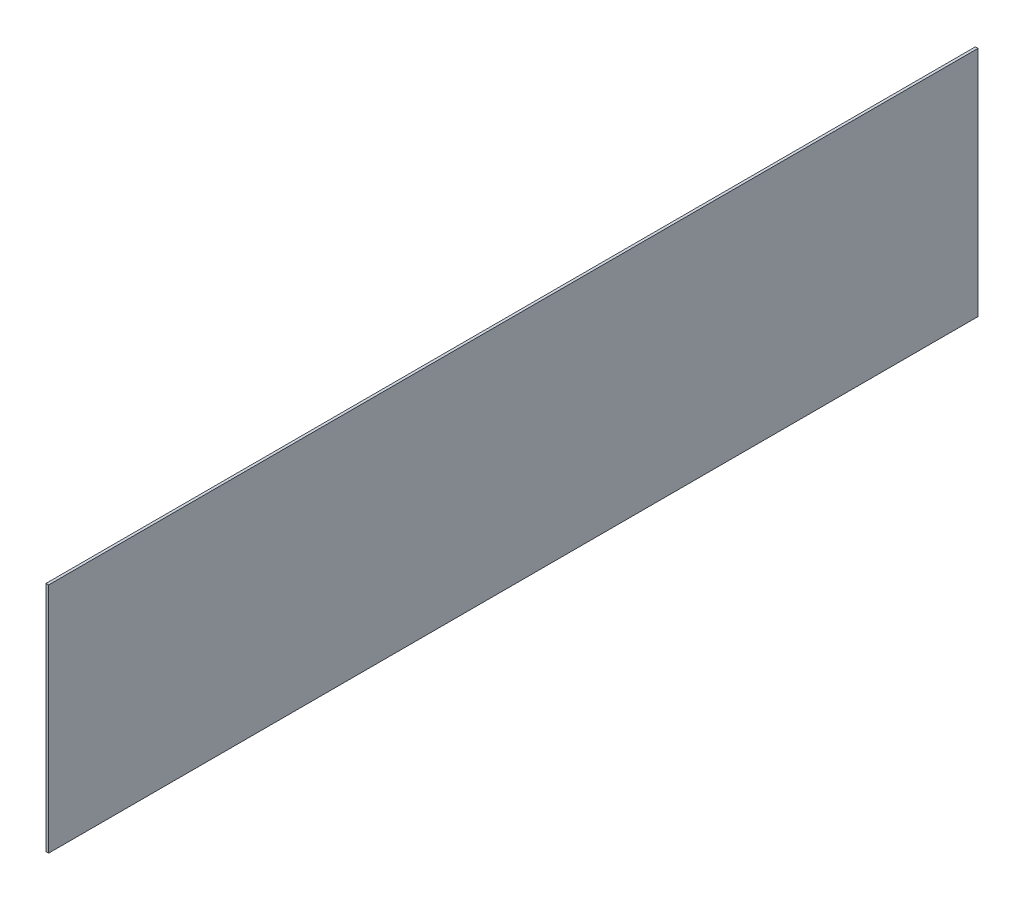
SolidWorks part; units mm, degrees
ref_plane "Front Plane" through (0, 0, 0) normal (0, 0, 1) x (1, 0, 0)
ref_plane "Top Plane" through (0, 0, 0) normal (0, 1, 0) x (1, 0, 0)
ref_plane "Right Plane" through (0, 0, 0) normal (1, 0, 0) x (0, 0, -1)
sketch "Sketch1" plane through (0, 0, 0) normal (1, 0, 0) x (0, 0, -1)
  line L1 (0, 0) -> (558.8, 0)
  line L2 (0, 0) -> (0, 139.7)
  line L3 (0, 139.7) -> (558.8, 139.7)
  line L4 (558.8, 0) -> (558.8, 139.7)
  dimension "D1" = 139.7
  dimension "D2" = 558.8
extrude "Boss-Extrude1" add sketch "Sketch1" along normal blind 1.5875
